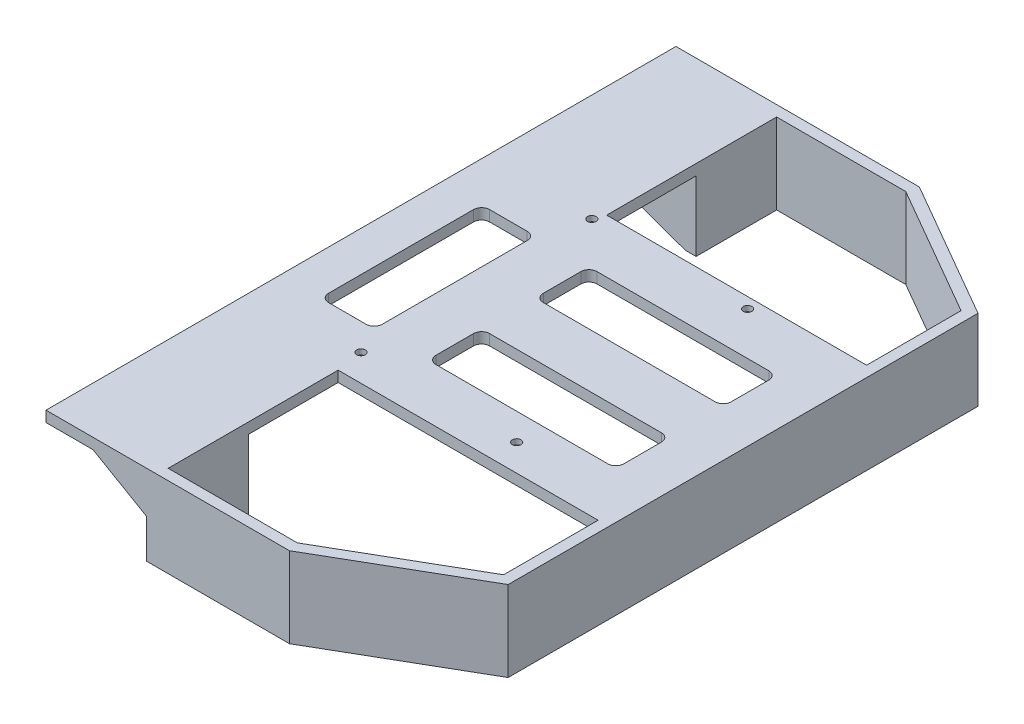
SolidWorks part; units mm, degrees
ref_plane "Front Plane" through (0, 0, 0) normal (0, 0, 1) x (1, 0, 0)
ref_plane "Top Plane" through (0, 0, 0) normal (0, 1, 0) x (1, 0, 0)
ref_plane "Right Plane" through (0, 0, 0) normal (1, 0, 0) x (0, 0, -1)
sketch "Sketch6" plane through (0, 0, 0) normal (0, 1, 0) x (1, 0, 0)
  line L0 (-142.3198, -87.5) -> (-142.3198, 87.5) construction
  line L1 (-142.3198, 87.5) -> (-90.67, 117.32) construction
  line L2 (-90.67, 117.32) -> (-37.5, 117.32) construction
  line L3 (-37.5, 117.32) -> (-37.5, 87.32) construction
  line L4 (-37.5, 87.32) -> (37.5, 87.32) construction
  line L5 (37.5, 87.32) -> (37.5, 117.32) construction
  line L6 (37.5, 117.32) -> (90.67, 117.32) construction
  line L7 (90.67, 117.32) -> (142.3198, 87.5) construction
  line L8 (142.3198, 87.5) -> (142.3198, -87.5) construction
  line L9 (-142.3198, 0) -> (142.3198, 0) construction
  line L10 (90.67, -117.32) -> (142.3198, -87.5) construction
  line L11 (37.5, -117.32) -> (90.67, -117.32) construction
  line L12 (-37.5, -87.32) -> (37.5, -87.32) construction
  line L13 (-37.5, -117.32) -> (-37.5, -87.32) construction
  line L14 (-90.67, -117.32) -> (-37.5, -117.32) construction
  line L15 (-142.3198, -87.5) -> (-90.67, -117.32) construction
  line L16 (37.5, -87.32) -> (37.5, -117.32) construction
  line L17 (0, -87.32) -> (37.5, -87.32)
  line L18 (37.5, -87.32) -> (37.5, -117.32)
  line L19 (37.5, -117.32) -> (90.67, -117.32)
  line L20 (90.67, -117.32) -> (142.3198, -87.5)
  line L21 (142.3198, -87.5) -> (142.3198, 87.5)
  line L23 (0, 87.32) -> (37.5, 87.32)
  line L24 (37.5, 87.32) -> (37.5, 117.32)
  line L25 (37.5, 117.32) -> (90.67, 117.32)
  line L26 (90.67, 117.32) -> (142.3198, 87.5)
  line L28 (0, -83.32) -> (41.5, -83.32)
  line L29 (41.5, -83.32) -> (41.5, -113.32)
  line L30 (41.5, -113.32) -> (89.5982, -113.32)
  line L31 (89.5982, -113.32) -> (138.3198, -85.1906)
  line L32 (138.3198, -85.1906) -> (138.3198, 85.1906)
  line L33 (89.5982, 113.32) -> (138.3198, 85.1906)
  line L34 (41.5, 113.32) -> (89.5982, 113.32)
  line L35 (41.5, 83.32) -> (41.5, 113.32)
  line L36 (0, 83.32) -> (41.5, 83.32)
  line L37 (0, 87.32) -> (0, 83.32)
  line L38 (0, -83.32) -> (0, -87.32)
  point P6 (0, 87.32)
  point P11 (0, 0)
  dimension "D1" = 30
  dimension "D2" = 75
  dimension "D3" = 53.17
  dimension "D4" = 87.5
  dimension "D5" = 59.64
  dimension "D6" = 120
  dimension "D7" = 4
extrude "Boss-Extrude1" add sketch "Sketch6" along normal blind 30
sketch "Sketch9" plane through (0, 0, 87.32) normal (0, 0, 1) x (1, 0, 0)
  line L0 (37.5, 0) -> (15, 8)
  line L1 (15, 8) -> (0, 8)
  line L2 (0, 30) -> (0, 0) construction
  line L3 (0, 0) -> (37.5, 0) construction
  line L4 (0, 8) -> (0, 0)
  line L5 (0, 0) -> (37.5, 0)
  dimension "D1" = 15
  dimension "D2" = 8
extrude "Cut-Extrude1" cut sketch "Sketch9" against normal up to next
sketch "Sketch10" plane through (0, 30, 0) normal (0, 1, 0) x (1, 0, 0)
  line L0 (37.5, -117.32) -> (90.67, -117.32) construction
  line L1 (0, -83.32) -> (41.5, -83.32)
  line L2 (0, -83.32) -> (0, -117.32)
  line L3 (0, -117.32) -> (41.5, -117.32)
  line L4 (41.5, -83.32) -> (41.5, -117.32)
  line L5 (41.5, -113.32) -> (41.5, -83.32) construction
extrude "Boss-Extrude3" add sketch "Sketch10" against normal blind 4
mirror "Mirror1" about plane through (0, 0, 0) normal (0, 0, 1) of "Boss-Extrude3", "Cut-Extrude1"
chamfer "Chamfer4" distance 20 angle 30 2 edges at (37.5, 26, 102.32) (37.5, 26, -102.32)
sketch "Sketch11" plane through (0, 30, 0) normal (0, 1, 0) x (1, 0, 0)
  line L0 (41.5, -83.32) -> (0, -83.32) construction
  line L1 (0, 83.32) -> (20.75, 83.32)
  line L2 (0, 83.32) -> (0, -83.32)
  line L3 (0, -83.32) -> (20.75, -83.32)
  line L4 (20.75, 83.32) -> (20.75, -83.32)
  point P8 (20.75, -83.32)
extrude "Boss-Extrude4" add sketch "Sketch11" against normal blind 4
sketch "Sketch12" plane through (0, 30, 0) normal (0, 1, 0) x (1, 0, 0)
  line L0 (20.75, -83.32) -> (20.75, 83.32) construction
  line L1 (20.75, 50) -> (138.3198, 50)
  line L2 (20.75, 50) -> (20.75, -50)
  line L3 (20.75, -50) -> (138.3198, -50)
  line L4 (138.3198, 50) -> (138.3198, -50)
  line L5 (138.3198, 85.1906) -> (138.3198, -85.1906) construction
  line L12 (41.5, 83.32) -> (20.75, 83.32)
  line L13 (41.5, 83.32) -> (41.5, 50)
  line L14 (41.5, 50) -> (20.75, 50)
  line L15 (20.75, 83.32) -> (20.75, 50)
  line L16 (41.5, -83.32) -> (20.75, -83.32)
  line L17 (41.5, -83.32) -> (41.5, -50)
  line L18 (41.5, -50) -> (20.75, -50)
  line L19 (20.75, -83.32) -> (20.75, -50)
  point P8 (20.75, 0)
  line M9 (41.5, -83.32) -> (20.75, -83.32)
  line M11 (20.75, -83.32) -> (20.75, 83.32)
  line M17 (138.3198, 85.1906) -> (138.3198, -85.1906)
  dimension "D1" = 100
extrude "Boss-Extrude5" add sketch "Sketch12" against normal blind 4 contours L3 L1 M11 M17 | L17 L3 M9 M11 | L14 L13 L12 L15
sketch "Sketch13" plane through (0, 30, 0) normal (0, 1, 0) x (1, 0, 0)
  line L5 (34.9099, 30) -> (14.9099, 30)
  line L10 (41.5, 50) -> (138.3198, 50) construction
  line L11 (54.9099, 30) -> (124.9099, 30)
  line L12 (54.9099, 30) -> (54.9099, 10)
  line L13 (54.9099, 10) -> (124.9099, 10)
  line L14 (124.9099, 30) -> (124.9099, 10)
  line L19 (0, 117.32) -> (0, -117.32) construction
  line L20 (0, 0) -> (142.3198, 0) construction
  line L21 (142.3198, -87.5) -> (142.3198, 87.5) construction
  line L22 (54.9099, -10) -> (124.9099, -10)
  line L23 (124.9099, -30) -> (124.9099, -10)
  line L24 (54.9099, -30) -> (124.9099, -30)
  line L25 (54.9099, -30) -> (54.9099, -10)
  line L26 (34.9099, 30) -> (34.9099, -30)
  line L27 (34.9099, -30) -> (14.9099, -30)
  line L28 (14.9099, 30) -> (14.9099, -30)
  point P14 (89.9099, 50)
  point P15 (89.9099, 30)
  dimension "D1" = 70
  dimension "D2" = 20
  dimension "D3" = 10
  dimension "D4" = 20
  dimension "D5" = 20
extrude "Cut-Extrude2" cut sketch "Sketch13" against normal blind 4
fillet "Fillet2" radius 3 12 edges at (124.9099, 28, -30) (124.9099, 28, 10) (54.9099, 28, 10) (54.9099, 28, -30) (54.9099, 28, 30) (54.9099, 28, -10) (124.9099, 28, -10) (124.9099, 28, 30) (34.9099, 28, 30) (34.9099, 28, -30) (14.9099, 28, 30) (14.9099, 28, -30)
sketch "Sketch14" plane through (0, 30, 0) normal (0, 1, 0) x (1, 0, 0)
  line L2 (142.3198, -87.5) -> (142.3198, 87.5) construction
  point P0 (142.3198, 0)
  line B0 (22.997, -50) -> (23.003, 50) construction
  line B1 (22.997, -50) -> (101.997, -50.0047) construction
  line B2 (101.997, -50.0047) -> (102.003, 49.9953) construction
  line B3 (23.003, 50) -> (102.003, 49.9953) construction
  line B4 (39.9976, -40.001) -> (40.0027, 45.999) construction
  line B5 (39.9976, -40.001) -> (97.9976, -40.0045) construction
  line B6 (97.9976, -40.0045) -> (98.0027, 45.9955) construction
  line B7 (40.0027, 45.999) -> (98.0027, 45.9955) construction
  circle B8 centre (39.9976, -40.001) radius 1.6
  circle B9 centre (97.9976, -40.0045) radius 1.6
  circle B10 centre (40.0027, 45.999) radius 1.6
  circle B11 centre (98.0027, 45.9955) radius 1.6
  dimension "D1" = 23
sketch_block_instance "Block-Jetson-Nano-1"
sketch_block "Block-Jetson-Nano" parameters "D3"=3.2, "D1"=100, "D2"=79, "D4"=4, "D5"=10, "D6"=17, "D7"=4
extrude "Cut-Extrude3" cut sketch "Sketch14" against normal blind 4
sketch "Sketch15" plane through (0, 26, 0) normal (0, -1, 0) x (1, 0, 0)
  line L0 (101.5027, -45.9955) -> (101.5027, -50)
  line L1 (41.5, -50) -> (138.3198, -50) construction
  line L2 (101.5027, -50) -> (94.5027, -50)
  line L3 (94.5027, -50) -> (94.5027, -45.9955)
  line L4 (94.5027, -45.9955) -> (101.5027, -45.9955)
  circle A0 centre (98.0027, -45.9955) radius 3.5 construction
  circle A1 centre (98.0027, -45.9955) radius 3.5
  circle A2 centre (40.0027, -45.999) radius 3.5
  circle A3 centre (39.9976, 40.001) radius 3.5
  circle A4 centre (97.9976, 40.0045) radius 3.5
  circle M9 centre (97.9976, 40.0045) radius 1.6
  circle M10 centre (40.0027, -45.999) radius 1.6
  circle M11 centre (98.0027, -45.9955) radius 1.6
  circle M12 centre (39.9976, 40.001) radius 1.6
  line M40 (41.5, -50) -> (138.3198, -50)
  dimension "D1" = 7
  dimension "D2" = 7
extrude "Cut-Extrude4" cut sketch "Sketch15" against normal blind 2 contours A2 M10 | A1 L3 L0 M40 | L4 A1 M11 | L4 A1 M11 | A4 M9 | A3 M12
